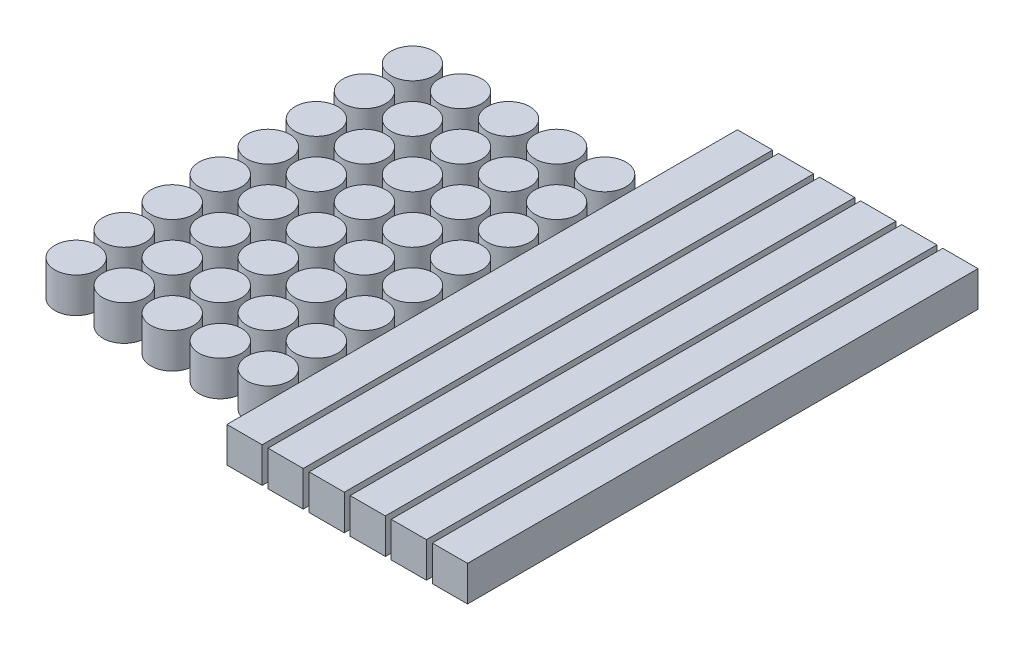
SolidWorks part; units mm, degrees
ref_plane "Front" through (0, 0, 0) normal (0, 0, 1) x (1, 0, 0)
ref_plane "Top" through (0, 0, 0) normal (0, 1, 0) x (1, 0, 0)
ref_plane "Right" through (0, 0, 0) normal (1, 0, 0) x (0, 0, -1)
sketch "Esboço1" plane through (0, 0, 0) normal (0, 1, 0) x (1, 0, 0)
  line L0 (13.632, 92.0109) -> (19.632, 92.0109)
  line L1 (6.632, 92.0109) -> (12.632, 92.0109)
  line L2 (6.632, 92.0109) -> (6.632, 5.0109)
  line L3 (6.632, 5.0109) -> (12.632, 5.0109)
  line L4 (12.632, 92.0109) -> (12.632, 5.0109)
  line L5 (13.632, 92.0109) -> (13.632, 5.0109)
  line L6 (13.632, 5.0109) -> (19.632, 5.0109)
  line L7 (19.632, 92.0109) -> (19.632, 5.0109)
  line L8 (20.632, 92.0109) -> (26.632, 92.0109)
  line L9 (20.632, 92.0109) -> (20.632, 5.0109)
  line L10 (20.632, 5.0109) -> (26.632, 5.0109)
  line L11 (26.632, 92.0109) -> (26.632, 5.0109)
  line L12 (27.632, 92.0109) -> (33.632, 92.0109)
  line L13 (27.632, 92.0109) -> (27.632, 5.0109)
  line L14 (27.632, 5.0109) -> (33.632, 5.0109)
  line L15 (33.632, 92.0109) -> (33.632, 5.0109)
  line L16 (34.632, 92.0109) -> (40.632, 92.0109)
  line L17 (34.632, 92.0109) -> (34.632, 5.0109)
  line L18 (34.632, 5.0109) -> (40.632, 5.0109)
  line L19 (40.632, 92.0109) -> (40.632, 5.0109)
  line L20 (41.632, 92.0109) -> (47.632, 92.0109)
  line L21 (41.632, 92.0109) -> (41.632, 5.0109)
  line L22 (41.632, 5.0109) -> (47.632, 5.0109)
  line L23 (47.632, 92.0109) -> (47.632, 5.0109)
  circle A0 centre (-30.8423, 16.7896) radius 3.6388
  circle A1 centre (-22.6549, 16.7896) radius 3.6388
  circle A2 centre (-14.4676, 16.7896) radius 3.6388
  circle A3 centre (-6.2803, 16.7896) radius 3.6388
  circle A4 centre (1.9071, 16.7896) radius 3.6388
  circle A5 centre (-22.6549, 24.9769) radius 3.6388
  circle A6 centre (-14.4676, 24.9769) radius 3.6388
  circle A7 centre (-6.2803, 24.9769) radius 3.6388
  circle A8 centre (1.9071, 24.9769) radius 3.6388
  circle A9 centre (-22.6549, 33.1642) radius 3.6388
  circle A10 centre (-14.4676, 33.1642) radius 3.6388
  circle A11 centre (-6.2803, 33.1642) radius 3.6388
  circle A12 centre (1.9071, 33.1642) radius 3.6388
  circle A13 centre (-22.6549, 41.3516) radius 3.6388
  circle A14 centre (-14.4676, 41.3516) radius 3.6388
  circle A15 centre (-6.2803, 41.3516) radius 3.6388
  circle A16 centre (1.9071, 41.3516) radius 3.6388
  circle A17 centre (-22.6549, 49.5389) radius 3.6388
  circle A18 centre (-14.4676, 49.5389) radius 3.6388
  circle A19 centre (-6.2803, 49.5389) radius 3.6388
  circle A20 centre (1.9071, 49.5389) radius 3.6388
  circle A21 centre (-22.6549, 57.7262) radius 3.6388
  circle A22 centre (-14.4676, 57.7262) radius 3.6388
  circle A23 centre (-6.2803, 57.7262) radius 3.6388
  circle A24 centre (1.9071, 57.7262) radius 3.6388
  circle A25 centre (-22.6549, 65.9136) radius 3.6388
  circle A26 centre (-14.4676, 65.9136) radius 3.6388
  circle A27 centre (-6.2803, 65.9136) radius 3.6388
  circle A28 centre (1.9071, 65.9136) radius 3.6388
  circle A29 centre (-22.6549, 74.1009) radius 3.6388
  circle A30 centre (-14.4676, 74.1009) radius 3.6388
  circle A31 centre (-6.2803, 74.1009) radius 3.6388
  circle A32 centre (1.9071, 74.1009) radius 3.6388
  circle A33 centre (-30.8423, 24.9769) radius 3.6388
  circle A34 centre (-30.8423, 33.1642) radius 3.6388
  circle A35 centre (-30.8423, 41.3516) radius 3.6388
  circle A36 centre (-30.8423, 49.5389) radius 3.6388
  circle A37 centre (-30.8423, 57.7262) radius 3.6388
  circle A38 centre (-30.8423, 65.9136) radius 3.6388
  circle A39 centre (-30.8423, 74.1009) radius 3.6388
  dimension "D1" = 5
  dimension "D3" = 6
  dimension "D4" = 87
  dimension "D2" = 8
  dimension "D5" = 6
extrude "Ressalto-extrusão1" add sketch "Esboço1" along normal blind 6
